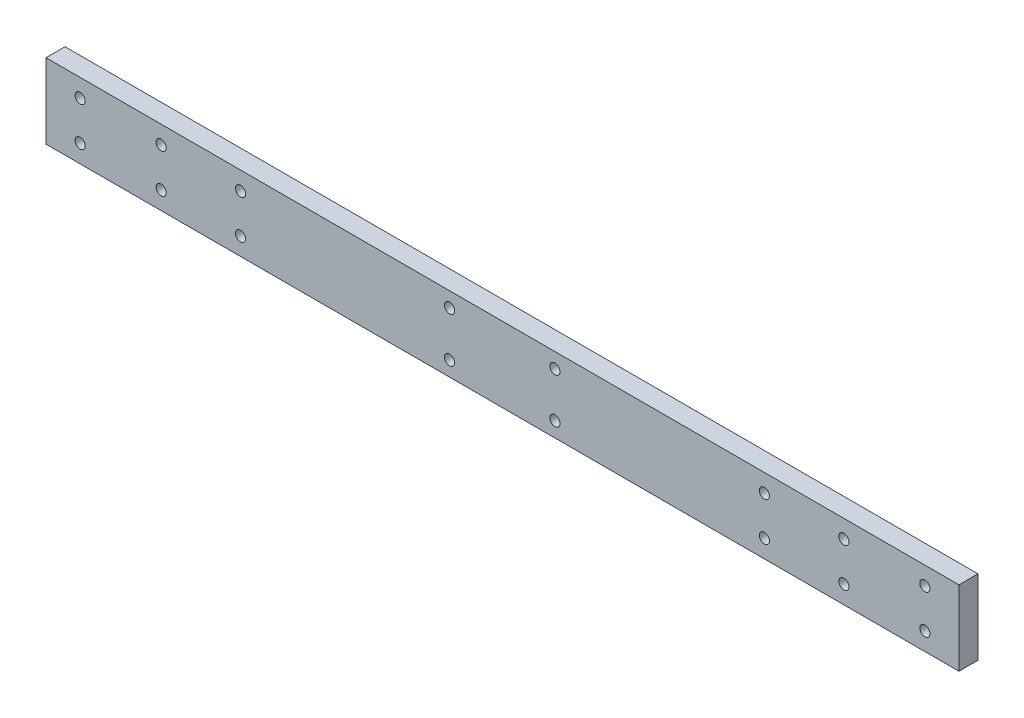
SolidWorks part; units mm, degrees
material "Balsa"
ref_plane "Front Plane" through (0, 0, 0) normal (0, 0, 1) x (1, 0, 0)
ref_plane "Top Plane" through (0, 0, 0) normal (0, 1, 0) x (1, 0, 0)
ref_plane "Right Plane" through (0, 0, 0) normal (1, 0, 0) x (0, 0, -1)
sketch "Sketch1" plane through (0, 0, 0) normal (0, 0, 1) x (1, 0, 0)
  line L1 (-40.7762, 235.9236) -> (264.0238, 235.9236)
  line L2 (-40.7762, 235.9236) -> (-40.7762, 210.9236)
  line L3 (-40.7762, 210.9236) -> (264.0238, 210.9236)
  line L4 (-40.7762, 235.9236) -> (-40.7762, -68.8764)
  line L5 (-40.7762, -68.8764) -> (264.0238, -68.8764)
  line L6 (264.0238, -68.8764) -> (264.0238, 235.9236)
  line L7 (264.0238, 235.9236) -> (-40.7762, 235.9236)
  line L11 (264.0238, 235.9236) -> (-40.7762, 235.9236)
  line L12 (264.0238, 235.9236) -> (264.0238, 210.9236)
  dimension "D1" = 0
extrude "Boss-Extrude1" add sketch "Sketch1" along normal blind 6.35 contours L12 L1 L2 L3
sketch "Sketch2" plane through (0, 0, 6.35) normal (0, 0, 1) x (1, 0, 0)
  circle A0 centre (225.5738, 216.9236) radius 1.7 construction
  circle A1 centre (225.5738, 229.9236) radius 1.7 construction
  circle A2 centre (252.6238, 229.9236) radius 1.7 construction
  circle A3 centre (252.6238, 216.9236) radius 1.7 construction
  circle A4 centre (225.5738, 216.9236) radius 1.7
  circle A5 centre (225.5738, 229.9236) radius 1.7
  circle A6 centre (252.6238, 229.9236) radius 1.7
  circle A7 centre (252.6238, 216.9236) radius 1.7
  circle A8 centre (-2.3262, 216.9236) radius 1.7 construction
  circle A9 centre (-29.3762, 216.9236) radius 1.7 construction
  circle A10 centre (-29.3762, 229.9236) radius 1.7 construction
  circle A11 centre (-2.3262, 229.9236) radius 1.7 construction
  circle A12 centre (-2.3262, 216.9236) radius 1.7
  circle A13 centre (-29.3762, 216.9236) radius 1.7
  circle A14 centre (-29.3762, 229.9236) radius 1.7
  circle A15 centre (-2.3262, 229.9236) radius 1.7
extrude "Cut-Extrude1" cut sketch "Sketch2" against normal blind 10
sketch "Sketch3" plane through (0, 0, 6.35) normal (0, 0, 1) x (1, 0, 0)
  circle A0 centre (225.5738, 216.9236) radius 1.7 construction
  circle A1 centre (225.5738, 229.9236) radius 1.7 construction
  circle A2 centre (225.5738, 216.9236) radius 1.7
  circle A3 centre (225.5738, 229.9236) radius 1.7
  circle A4 centre (199.0505, 216.9236) radius 1.7 construction
  circle A5 centre (199.0505, 229.9236) radius 1.7 construction
  circle A6 centre (199.0505, 216.9236) radius 1.7
  circle A7 centre (199.0505, 229.9236) radius 1.7
  circle A8 centre (129.1238, 215.9236) radius 1.7 construction
  circle A9 centre (129.1238, 230.9236) radius 1.7 construction
  circle A10 centre (129.1238, 215.9236) radius 1.7
  circle A11 centre (129.1238, 230.9236) radius 1.7
  circle A12 centre (93.9602, 215.9236) radius 1.7 construction
  circle A13 centre (93.9602, 230.9236) radius 1.7 construction
  circle A14 centre (93.9602, 215.9236) radius 1.7
  circle A15 centre (93.9602, 230.9236) radius 1.7
  circle A16 centre (24.1969, 229.8406) radius 1.7 construction
  circle A17 centre (24.1969, 229.8406) radius 1.7
  circle A18 centre (24.1562, 216.8406) radius 1.7 construction
  circle A19 centre (24.1562, 216.8406) radius 1.7
extrude "Cut-Extrude2" cut sketch "Sketch3" against normal blind 22
